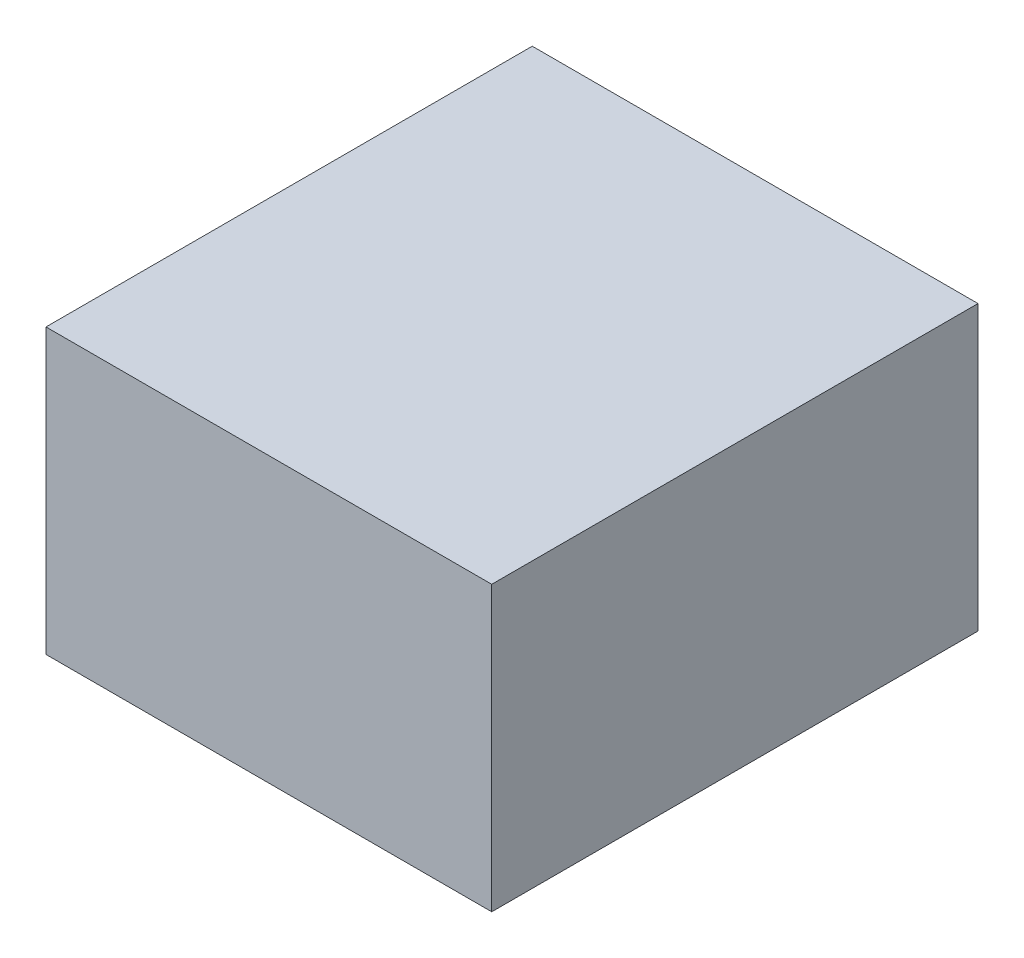
SolidWorks part; units mm, degrees
ref_plane "Front Plane" through (0, 0, 0) normal (0, 0, 1) x (1, 0, 0)
ref_plane "Top Plane" through (0, 0, 0) normal (0, 1, 0) x (1, 0, 0)
ref_plane "Right Plane" through (0, 0, 0) normal (1, 0, 0) x (0, 0, -1)
sketch "Sketch1" plane through (0, 0, 0) normal (0, 0, 1) x (1, 0, 0)
  line L1 (139.7, -88.9) -> (-139.7, -88.9)
  line L2 (139.7, -88.9) -> (139.7, 88.9)
  line L3 (139.7, 88.9) -> (-139.7, 88.9)
  line L4 (-139.7, -88.9) -> (-139.7, 88.9)
  line L5 (139.7, -88.9) -> (-139.7, 88.9) construction
  line L6 (139.7, 88.9) -> (-139.7, -88.9) construction
  point P0 (0, 0)
  dimension "D1" = 177.8
  dimension "D2" = 279.4
extrude "Boss-Extrude1" add sketch "Sketch1" along normal blind 304.8
